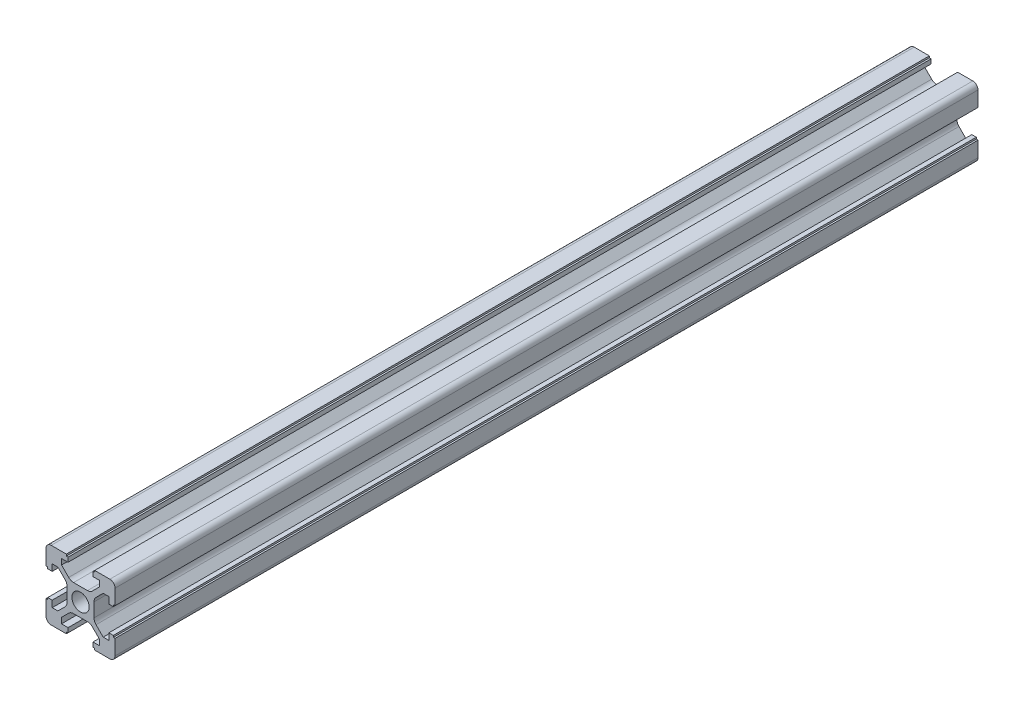
SolidWorks part; units mm, degrees
material "6063-O"
ref_plane "Front Plane" through (0, 0, 0) normal (0, 0, 1) x (1, 0, 0)
ref_plane "Top Plane" through (0, 0, 0) normal (0, 1, 0) x (1, 0, 0)
ref_plane "Right Plane" through (0, 0, 0) normal (1, 0, 0) x (0, 0, -1)
sketch "Sketch1" plane through (0, 0, 0) normal (0, 0, 1) x (1, 0, 0)
  line L0 (10, -4.1) -> (10, -8.5)
  line L1 (4.1, 10) -> (8.5, 10)
  line L2 (8.5, -10) -> (4.1, -10)
  line L3 (-8.5, -10) -> (-4.1, -10)
  line L4 (10, 8.5) -> (10, 4.1)
  line L7 (8.5, 10) -> (4.1, 10)
  line L8 (5.5, 6.5607) -> (3.4251, 4.4858)
  line L9 (8.5, 10) -> (4.1, 10)
  line L10 (3.9, 2.0109) -> (3.9, -2.0109)
  line L11 (2.0109, -3.9) -> (-2.0109, -3.9)
  line L12 (-3.9, -2.0109) -> (-3.9, 2.0109)
  line L13 (-2.0109, 3.9) -> (2.8393, 3.9)
  line L14 (2.5, 0) -> (22.2403, 0) construction
  line L15 (3.6, 9.5) -> (3.6, 8.2)
  line L16 (9.5, 3.6) -> (8.2, 3.6)
  line L17 (8.2, 3.6) -> (8.2, 5.5)
  line L18 (8.2, 5.5) -> (6.5607, 5.5)
  line L19 (10, -4.1) -> (10, -8.5)
  line L20 (4.1, 9.5) -> (3.6, 9.5)
  line L21 (4.1, 10) -> (4.1, 9.5)
  line L22 (8.5, 10) -> (4.1, 10)
  line L23 (10, 4.1) -> (9.5, 4.1)
  line L24 (9.5, 4.1) -> (9.5, 3.6)
  line L25 (5.5, 8.2) -> (5.5, 6.5607)
  line L26 (3.6, 8.2) -> (5.5, 8.2)
  line L27 (4.4858, 3.4251) -> (6.5607, 5.5)
  line L28 (10, -8.5) -> (10, -4.1)
  line L29 (6.5607, -5.5) -> (4.4858, -3.4251)
  line L30 (10, -8.5) -> (10, -4.1)
  line L31 (2.0109, -3.9) -> (-2.0109, -3.9)
  line L32 (3.9, 2.8393) -> (3.9, -2.0109)
  line L33 (9.5, -3.6) -> (8.2, -3.6)
  line L34 (3.6, -9.5) -> (3.6, -8.2)
  line L35 (3.6, -8.2) -> (5.5, -8.2)
  line L36 (5.5, -8.2) -> (5.5, -6.5607)
  line L37 (9.5, -4.1) -> (9.5, -3.6)
  line L38 (10, -4.1) -> (9.5, -4.1)
  line L39 (10, -8.5) -> (10, -4.1)
  line L40 (4.1, -10) -> (4.1, -9.5)
  line L41 (4.1, -9.5) -> (3.6, -9.5)
  line L42 (8.2, -5.5) -> (6.5607, -5.5)
  line L43 (8.2, -3.6) -> (8.2, -5.5)
  line L44 (3.4251, -4.4858) -> (5.5, -6.5607)
  line L45 (-4.1, -10) -> (-8.5, -10)
  line L46 (-10, -8.5) -> (-10, -4.1)
  line L47 (-8.5, -10) -> (-4.1, -10)
  line L48 (-5.5, -6.5607) -> (-3.4251, -4.4858)
  line L49 (-8.5, -10) -> (-4.1, -10)
  line L50 (-3.9, -2.0109) -> (-3.9, 2.0109)
  line L51 (2.0109, -3.9) -> (-2.0109, -3.9)
  line L52 (-3.6, -9.5) -> (-3.6, -8.2)
  line L53 (-9.5, -3.6) -> (-8.2, -3.6)
  line L54 (-8.2, -3.6) -> (-8.2, -5.5)
  line L55 (-8.2, -5.5) -> (-6.5607, -5.5)
  line L56 (-4.1, -9.5) -> (-3.6, -9.5)
  line L57 (-4.1, -10) -> (-4.1, -9.5)
  line L58 (-8.5, -10) -> (-4.1, -10)
  line L59 (-10, -4.1) -> (-9.5, -4.1)
  line L60 (-9.5, -4.1) -> (-9.5, -3.6)
  line L61 (-5.5, -8.2) -> (-5.5, -6.5607)
  line L62 (-3.6, -8.2) -> (-5.5, -8.2)
  line L63 (-4.4858, -3.4251) -> (-6.5607, -5.5)
  line L64 (-10, 4.1) -> (-10, 8.5)
  line L65 (-8.5, 10) -> (-4.1, 10)
  line L66 (-10, 8.5) -> (-10, 4.1)
  line L67 (-6.5607, 5.5) -> (-4.4858, 3.4251)
  line L68 (-10, 8.5) -> (-10, 4.1)
  line L69 (-2.0109, 3.9) -> (2.0109, 3.9)
  line L70 (-3.9, -2.0109) -> (-3.9, 2.0109)
  line L71 (-9.5, 3.6) -> (-8.2, 3.6)
  line L72 (-3.6, 9.5) -> (-3.6, 8.2)
  line L73 (-3.6, 8.2) -> (-5.5, 8.2)
  line L74 (-5.5, 8.2) -> (-5.5, 6.5607)
  line L75 (-9.5, 4.1) -> (-9.5, 3.6)
  line L76 (-10, 4.1) -> (-9.5, 4.1)
  line L77 (-10, 8.5) -> (-10, 4.1)
  line L78 (-4.1, 10) -> (-4.1, 9.5)
  line L79 (-4.1, 9.5) -> (-3.6, 9.5)
  line L80 (-8.2, 5.5) -> (-6.5607, 5.5)
  line L81 (-8.2, 3.6) -> (-8.2, 5.5)
  line L82 (-3.4251, 4.4858) -> (-5.5, 6.5607)
  line L83 (4.1, -10) -> (8.5, -10)
  arc A0 (2.0109, -3.9) -> (3.4251, -4.4858) centre (2.0109, -5.9) cw
  arc A1 (4.4858, -3.4251) -> (3.9, -2.0109) centre (5.9, -2.0109) cw
  arc A2 (3.9, 2.0109) -> (4.4858, 3.4251) centre (5.9, 2.0109) cw
  arc A3 (2.0109, 3.9) -> (3.4251, 4.4858) centre (2.0109, 5.9) ccw
  arc A4 (-2.0109, 3.9) -> (-3.4251, 4.4858) centre (-2.0109, 5.9) cw
  arc A5 (-4.4858, 3.4251) -> (-3.9, 2.0109) centre (-5.9, 2.0109) cw
  arc A6 (-3.4251, -4.4858) -> (-2.0109, -3.9) centre (-2.0109, -5.9) cw
  arc A7 (-3.9, -2.0109) -> (-4.4858, -3.4251) centre (-5.9, -2.0109) cw
  circle A8 centre (0, 0) radius 2.5
  arc A9 (-8.5, -10) -> (-10, -8.5) centre (-8.5, -8.5) cw
  arc A10 (-10, 8.5) -> (-8.5, 10) centre (-8.5, 8.5) cw
  arc A11 (8.5, 10) -> (10, 8.5) centre (8.5, 8.5) cw
  arc A12 (8.5, -10) -> (10, -8.5) centre (8.5, -8.5) ccw
  point P0 (0, 0)
  point P86 (0, 0)
  point P107 (10, -10)
  dimension "D3" = 2
  dimension "D5" = 5
  dimension "D2" = 1.5
  dimension "D8" = 1.5
  dimension "D6" = 4
  dimension "D7" = 6.1
  dimension "D11" = 0.5
  dimension "D12" = 0.5
extrude "Boss-Extrude2" add sketch "Sketch1" along normal blind 250
